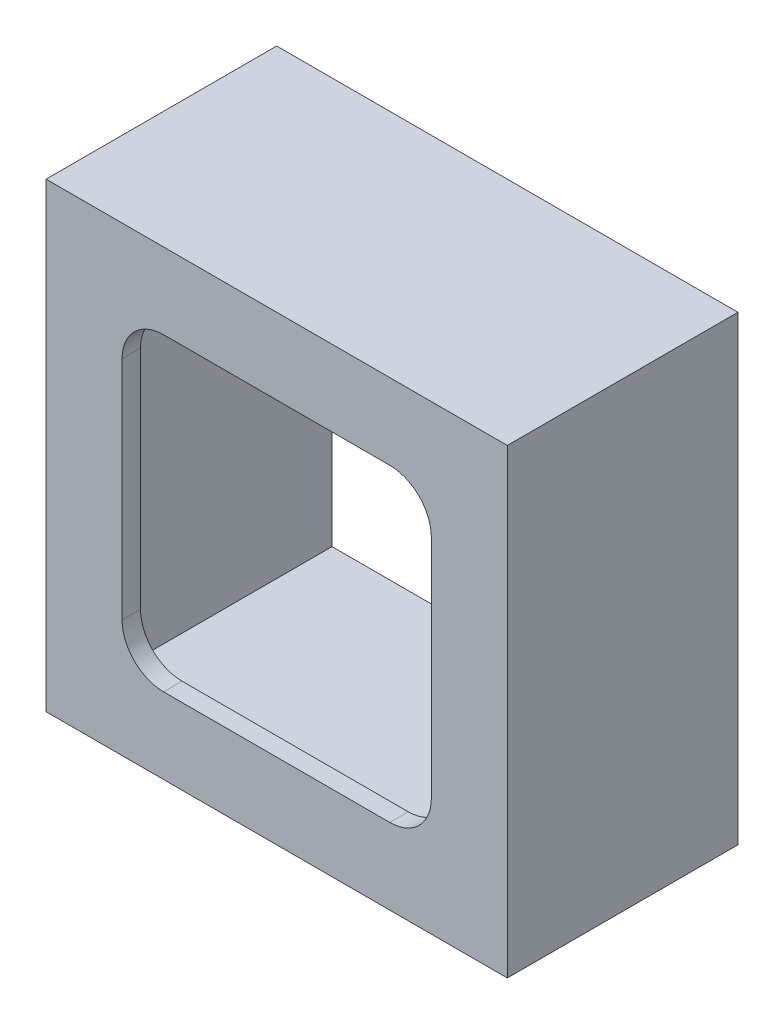
SolidWorks part; units mm, degrees
ref_plane "Front Plane" through (0, 0, 0) normal (0, 0, 1) x (1, 0, 0)
ref_plane "Top Plane" through (0, 0, 0) normal (0, 1, 0) x (1, 0, 0)
ref_plane "Right Plane" through (0, 0, 0) normal (1, 0, 0) x (0, 0, -1)
sketch "Sketch1" plane through (0, 0, 0) normal (0, 0, 1) x (1, 0, 0)
  line L0 (12.2635, 16.7635) -> (-12.2635, 16.7635) construction
  line L1 (16.7635, -12.2635) -> (16.7635, 12.2635) construction
  line L2 (-12.2635, -16.7635) -> (12.2635, -16.7635) construction
  line L3 (-16.7635, 12.2635) -> (-16.7635, -12.2635) construction
  line L4 (12.2635, 16.7635) -> (-12.2635, 16.7635)
  line L5 (16.7635, -12.2635) -> (16.7635, 12.2635)
  line L6 (-12.2635, -16.7635) -> (12.2635, -16.7635)
  line L7 (-16.7635, 12.2635) -> (-16.7635, -12.2635)
  line L8 (-23, 23) -> (-23, -23) construction
  line L9 (25, 25) -> (-25, 25)
  line L10 (25, 25) -> (25, -25)
  line L11 (25, -25) -> (-25, -25)
  line L12 (-25, 25) -> (-25, -25)
  line L13 (25, 25) -> (-25, -25) construction
  line L14 (25, -25) -> (-25, 25) construction
  line L15 (23, 23) -> (-23, 23) construction
  arc A0 (-12.2635, 16.7635) -> (-16.7635, 12.2635) centre (-12.2635, 12.2635) ccw construction
  arc A1 (16.7635, 12.2635) -> (12.2635, 16.7635) centre (12.2635, 12.2635) ccw construction
  arc A2 (12.2635, -16.7635) -> (16.7635, -12.2635) centre (12.2635, -12.2635) ccw construction
  arc A3 (-16.7635, -12.2635) -> (-12.2635, -16.7635) centre (-12.2635, -12.2635) ccw construction
  arc A4 (-12.2635, 16.7635) -> (-16.7635, 12.2635) centre (-12.2635, 12.2635) ccw
  arc A5 (16.7635, 12.2635) -> (12.2635, 16.7635) centre (12.2635, 12.2635) ccw
  arc A6 (12.2635, -16.7635) -> (16.7635, -12.2635) centre (12.2635, -12.2635) ccw
  arc A7 (-16.7635, -12.2635) -> (-12.2635, -16.7635) centre (-12.2635, -12.2635) ccw
  point P4 (0, 0)
  dimension "D1" = 2
  dimension "D2" = 2
extrude "Boss-Extrude1" add sketch "Sketch1" against normal up to surface (2 mm away)
sketch "Sketch2" plane through (0, 0, -2) normal (0, 0, -1) x (-1, 0, 0)
  line L5 (-25, 25) -> (25, 25)
  line L6 (-25, 25) -> (-25, -25)
  line L7 (-25, -25) -> (25, -25)
  line L8 (25, 25) -> (25, -25)
  line L9 (-19, 19) -> (19, 19)
  line L10 (-19, 19) -> (-19, -19)
  line L11 (-19, -19) -> (19, -19)
  line L12 (19, 19) -> (19, -19)
extrude "Boss-Extrude2" add sketch "Sketch2" along normal blind 23
